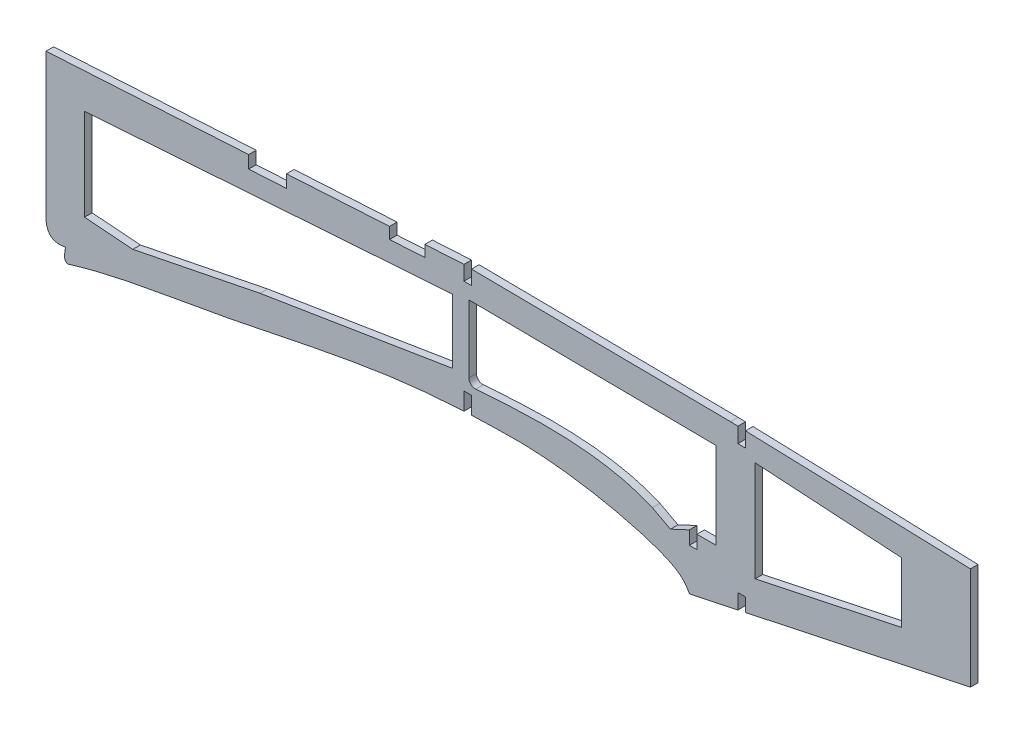
SolidWorks part; units mm, degrees
ref_plane "Front Plane" through (0, 0, 0) normal (0, 0, 1) x (1, 0, 0)
ref_plane "Top Plane" through (0, 0, 0) normal (0, 1, 0) x (1, 0, 0)
ref_plane "Right Plane" through (0, 0, 0) normal (1, 0, 0) x (0, 0, -1)
sketch "Sketch1" plane through (0, 0, 0) normal (0, 0, 1) x (1, 0, 0)
  line L0 (0, 0) -> (110, 0) construction
  line L1 (110, 0) -> (110, 21) construction
  line L2 (0, 0) -> (110, 21)
  line L3 (23.5, 17.3139) -> (20, 16.6457)
  line L4 (0, 0) -> (20, 0)
  line L5 (20, 0) -> (20, 67.15) construction
  line L6 (0, 0) -> (0, 67.15) construction
  line L7 (0, 67.15) -> (110, 67.15) construction
  line L8 (110, 61.55) -> (110, 67.15)
  line L9 (0, 67.15) -> (110, 61.55)
  line L10 (23.5, 53.9381) -> (81.5, 50.9854)
  line L11 (81.5, 50.9854) -> (81.5, 28.3866)
  line L12 (23.5, 53.9381) -> (23.5, 17.3139)
  line L13 (23.5, 17.3139) -> (81.5, 28.3866)
  line L14 (110, 21) -> (110, 61.55) construction
  line L15 (112, 61.4482) -> (112, 21.3818)
  line L16 (110, 61.55) -> (112, 61.4482)
  line L17 (110, 21) -> (112, 21.3818)
  line L18 (10.9, 67.15) -> (10.9, 0)
  line L19 (0, 67.15) -> (-82.3902, 71.3444)
  line L20 (0, 0) -> (-182.0672, -34.7583)
  line L21 (-86.7, -36.2944) -> (-86.7, -57.7944)
  line L22 (-93.05, 89.1409) -> (-93.05, -40.6456)
  line L23 (-70.5516, 60.184) -> (7.4462, 55.0566)
  line L24 (-89.4413, 54.3923) -> (-89.4413, 37.6042)
  line L25 (-65.3332, 22.0194) -> (-42.2468, 20.2821) construction
  line L26 (-42.2468, 20.2821) -> (-21.4079, 14.5616) construction
  line L27 (-21.4079, 14.5616) -> (-8.5368, 8.8411) construction
  line L28 (-8.5368, 8.8411) -> (-2.8162, 7.0023) construction
  line L29 (-2.8162, 7.0023) -> (0, 0) construction
  line L30 (-235.9653, 18.0968) -> (-234.0715, 53.1142)
  line L31 (-238.05, 59.4719) -> (-238.05, 21) construction
  line L32 (-921.7383, -124.7627) -> (144.2786, -161.9889) construction
  line L34 (-226.3459, 60.184) -> (-104.3294, 60.184)
  line L35 (-82.0567, 37.6042) -> (-82.7237, 57.9466)
  line L36 (-82.3902, 71.3444) -> (-103.6, 72.4242)
  line L37 (-103.6, 72.4242) -> (-103.6, 67.1242)
  line L38 (-103.6, 67.1242) -> (-117.6, 67.1242)
  line L39 (-117.6, 67.1242) -> (-117.6, 72.6011)
  line L40 (-117.6, 72.6011) -> (-158.5, 72.6011)
  line L41 (-158.5, 72.6011) -> (-158.5, 68.6011)
  line L42 (-158.5, 68.6011) -> (-173.5, 69.3647)
  line L43 (-173.5, 69.3647) -> (-173.5, 73.3311)
  line L44 (-173.5, 73.3311) -> (-250.6778, 73.3311)
  line L45 (-250.6778, 73.3311) -> (-251.1351, 64.35)
  line L46 (-251.1351, 64.35) -> (-249.1426, 59.4719)
  line L47 (-249.1426, 59.4719) -> (-253.0614, 11.9612)
  spline_without_curve S0
  spline S1 degree 3 poles (-62.7428, 33.1676) (-50.008, 31.9642) (-31.0962, 32.5015) (-14.1751, 24.9914) (-9.6822, 22.192) knots 0 0 0 0 0.709755 1 1 1 1
  spline S2 degree 3 poles (-9.6822, 22.192) (-6.8917, 20.9668) (-4.0654, 23.2801) (1.077, 24.0309) (6.7349, 23.1276) (13.0796, 25.9871) (10.9, 30.3114) knots 0 0 0 0 0.304362 0.391412 0.603771 1 1 1 1
  spline S3 degree 3 poles (-65.3332, 22.0194) (-77.4805, 22.6509) (-98.8967, 23.1079) (-139.7694, 19.7032) (-187.7649, 10.9991) (-227.3069, 7.5749) (-246.6861, 2.6333) knots 0 0 0 0 0.199692 0.351003 0.672194 1 1 1 1
  spline S4 degree 3 poles (-62.7428, 33.1676) (-67.9368, 33.6388) (-74.1452, 31.6619) (-82.8627, 34.4448) (-82.0567, 37.6042) knots 0 0 0 0 0.65977 1 1 1 1
  spline S5 degree 3 poles (-104.3294, 60.184) (-100.5301, 59.5513) (-93.8007, 61.9485) (-88.7866, 56.5953) (-89.4413, 54.3923) knots 0 0 0 0 0.661964 1 1 1 1
  spline S6 degree 3 poles (-104.3294, 33.547) (-100.6826, 33.3941) (-97.3824, 32.6768) (-91.1309, 33.381) (-89.6784, 34.473) (-89.4413, 37.6042) knots 0 0 0 0 0.555991 0.846219 1 1 1 1
  spline S7 degree 3 poles (-104.3294, 33.547) (-116.4931, 34.3961) (-139.9294, 30.8214) (-169.9623, 27.1478) (-193.8607, 26.9431) (-204.0402, 24.0023) (-211.1217, 23.2564) (-214.8026, 19.376) (-215.2918, 15.9456) (-214.9447, 14.6164) (-218.1891, 14.6988) (-221.7312, 14.9192) (-230.6867, 16.3937) (-236.4685, 15.9971) (-235.9653, 18.0968) knots 0 0 0 0 0.241116 0.431915 0.666521 0.747659 0.783153 0.799752 0.821748 0.858269 0.866885 0.907914 0.932706 1 1 1 1
  spline S8 degree 3 poles (-82.7237, 57.9466) (-82.8248, 63.2577) (-71.0235, 59.3637) (-70.5516, 60.184) knots 0 0 0 0 1 1 1 1
  spline S9 degree 2 poles (7.4462, 55.0566) (12.5645, 55.8042) (10.9, 50.909) knots 0 0 0 1 1 1
  spline S10 degree 3 poles (-234.0715, 53.1142) (-234.3359, 55.4474) (-232.0516, 60.1047) (-228.0459, 60.2249) (-226.3459, 60.184) knots 0 0 0 0 0.618254 1 1 1 1
  spline S11 degree 2 poles (-253.0614, 11.9612) (-252.6953, 7.068) (-247.464, 8.0018) knots 0 0 0 1 1 1
  spline S12 degree 3 poles (-246.6861, 2.6333) (-248.9283, 3.1544) (-247.5659, 6.6016) (-247.464, 8.0018) knots 0 0 0 0 1 1 1 1
  point P55 (-93.05, 46.4253)
  dimension "D1" = 110
  dimension "D2" = 21
  dimension "D3" = 12.6
  dimension "D4" = 20
  dimension "D5" = 67.15
  dimension "D6" = 5.6
  dimension "D7" = 110
  dimension "D8" = 12
  dimension "D9" = 3.5
  dimension "D10" = 58
  dimension "D11" = 2
  dimension "D12" = 12.6
  dimension "D13" = 97.6
  dimension "D14" = 6.35
  dimension "D15" = 14
  dimension "D16" = 145
  dimension "D17" = 15
  dimension "D18" = 40.9
  dimension "D19" = 10.55
  dimension "D20" = 5.3
  dimension "D21" = 4
sketch "Sketch2" plane through (0, 0, 0) normal (0, 0, 1) x (1, 0, 0)
  line L0 (0, 0) -> (110, 21) construction
  line L1 (0, 0) -> (110, 21)
  line L2 (112, 61.4482) -> (112, 21.3818) construction
  line L3 (112, 61.4482) -> (112, 21.3818)
  line L4 (-70.5516, 60.184) -> (7.4462, 55.0566) construction
  line L5 (110, 21) -> (112, 21.3818) construction
  line L6 (110, 21) -> (112, 21.3818)
  line L7 (110, 61.55) -> (112, 61.4482) construction
  line L8 (110, 61.55) -> (112, 61.4482)
  line L9 (0, 67.15) -> (110, 61.55) construction
  line L10 (0, 67.15) -> (110, 61.55)
  line L11 (0, 67.15) -> (-82.3902, 71.3444) construction
  line L12 (0, 67.15) -> (-82.3902, 71.3444)
  line L13 (-82.3902, 71.3444) -> (-103.6, 72.4242) construction
  line L14 (-82.3902, 71.3444) -> (-103.6, 72.4242)
  line L15 (-103.6, 72.4242) -> (-103.6, 67.3782)
  line L16 (-103.6, 67.3782) -> (-117.6, 67.3782)
  line L17 (-117.6, 67.3782) -> (-117.6, 72.6011)
  line L18 (-117.6, 72.6011) -> (-158.5, 72.6011)
  line L19 (-158.5, 72.6011) -> (-158.5, 69.3647)
  line L20 (-158.5, 69.3647) -> (-173.5, 69.3647)
  line L21 (-173.5, 69.3647) -> (-173.5, 73.3311)
  line L22 (-173.5, 73.3311) -> (-250.6778, 73.3311) construction
  line L23 (-173.5, 73.3311) -> (-250.6778, 73.3311)
  line L24 (-250.6778, 73.3311) -> (-253.0614, 11.9612)
  line L25 (-89.4413, 54.3923) -> (-89.4413, 37.6042) construction
  line L26 (-226.3459, 60.184) -> (-104.3294, 60.184) construction
  line L27 (-235.9653, 18.0968) -> (-234.0715, 53.1142) construction
  line L28 (-89.4413, 54.3923) -> (-89.4413, 37.6042)
  line L29 (-226.3459, 60.184) -> (-104.3294, 60.184)
  line L30 (-235.9653, 18.0968) -> (-234.0715, 53.1142)
  line L31 (-82.0567, 37.6042) -> (-82.7237, 57.9466) construction
  line L32 (-70.5516, 60.184) -> (7.4462, 55.0566)
  line L33 (-82.0567, 37.6042) -> (-82.7237, 57.9466)
  line L34 (10.9, 50.909) -> (10.9, 30.3114)
  line L35 (81.5, 50.9854) -> (81.5, 28.3866) construction
  line L36 (23.5, 17.3139) -> (81.5, 28.3866) construction
  line L37 (23.5, 53.9381) -> (81.5, 50.9854) construction
  line L38 (23.5, 53.9381) -> (23.5, 17.3139) construction
  line L39 (81.5, 48.1342) -> (81.5, 30.8681)
  line L40 (27.0626, 17.994) -> (79.0626, 27.9213)
  line L41 (26.6525, 53.7776) -> (78.6525, 51.1303)
  line L42 (23.5, 50.7815) -> (23.5, 20.9408)
  line L43 (-158.5, 72.6011) -> (-158.5, 68.6011) construction
  arc A0 (26.6525, 53.7776) -> (23.5, 50.7815) centre (26.5, 50.7815) ccw
  arc A1 (27.0626, 17.994) -> (23.5, 20.9408) centre (26.5, 20.9408) cw
  arc A2 (81.5, 30.8681) -> (79.0626, 27.9213) centre (78.5, 30.8681) cw
  arc A3 (81.5, 48.1342) -> (78.6525, 51.1303) centre (78.5, 48.1342) ccw
  parabola Q0 (-253.0614, 11.9612) -> (-247.464, 8.0018) focus (-250.6889, 9.8561) apex (-251.6748, 8.6753) construction
  parabola Q1 (-253.0614, 11.9612) -> (-247.464, 8.0018) focus (-250.6889, 9.8561) apex (-251.6748, 8.6753)
  parabola Q2 (7.4462, 55.0566) -> (10.9, 50.909) focus (10.2347, 53.865) apex (10.8693, 54.3929) construction
  parabola Q3 (7.4462, 55.0566) -> (10.9, 50.909) focus (10.2347, 53.865) apex (10.8693, 54.3929)
  spline S0 degree 3 poles (1215.9924, 1366.2087) (-1689.2719, -1445.9602) (1160.7038, 1491.2702) (-1612.7605, -1453.4516) knots -5.972872 -5.972872 -5.972872 -5.972872 7.300913 7.300913 7.300913 7.300913 only from (-246.6861, 2.6333) to (-247.464, 8.0018) construction
  spline S1 degree 3 poles (-246.6861, 2.6333) (-248.9283, 3.1544) (-247.5659, 6.6016) (-247.464, 8.0018) knots 0 0 0 0 1 1 1 1
  spline S2 degree 3 poles (175.3636, 1967.872) (391.9741, -245.9956) (130.7811, 42.2402) (-139.7694, 19.7032) (-325.1272, -13.9116) (-514.1452, 28.671) (-309.5796, -1983.4136) knots -3.777296 -3.777296 -3.777296 -3.777296 0.199692 0.351003 0.672194 3.290466 3.290466 3.290466 3.290466 only from (-65.3332, 22.0194) to (-246.6861, 2.6333) construction
  spline S3 degree 3 poles (-65.3332, 22.0194) (-77.4805, 22.6509) (-98.8967, 23.1079) (-139.7694, 19.7032) (-187.7649, 10.9991) (-227.3069, 7.5749) (-246.6861, 2.6333) knots 0 0 0 0 0.199692 0.351003 0.672194 1 1 1 1
  spline S4 degree 5 poles (1876.0426, 360.0904) (-1729.8867, -1179.746) (583.5253, 1803.2982) (78.4446, -2000.9415) (-313.5377, 2017.6127) (349.0217, -1969.1752) knots -2.469726 -2.469726 -2.469726 -2.469726 -2.469726 -2.469726 2.883008 2.883008 2.883008 2.883008 2.883008 2.883008 only from (-65.3332, 22.0194) to (0, 0) construction
  spline S5 degree 5 poles (-65.3332, 22.0194) (-42.2468, 20.2821) (-21.4079, 14.5616) (-8.5368, 8.8411) (-2.8162, 7.0023) (0, 0) knots 0 0 0 0 0 0 1 1 1 1 1 1
  spline S6 degree 3 poles (-2003.4226, -592.8129) (-74.6134, 83.2569) (-127.2178, 29.3158) (-83.3934, 34.2526) (-91.8628, 46.616) (-191.2637, 2034.7775) knots -4.772522 -4.772522 -4.772522 -4.772522 0.555991 0.846219 2.237697 2.237697 2.237697 2.237697 only from (-104.3294, 33.547) to (-89.4413, 37.6042) construction
  spline S7 degree 3 poles (-884.1428, -1800.4231) (147.9483, 84.9453) (-58.8059, 40.7444) (-169.9623, 27.1478) (-193.8607, 26.9431) (-204.0402, 24.0023) (-211.1217, 23.2564) (-214.8026, 19.376) (-215.2918, 15.9456) (-214.9447, 14.6164) (-218.1891, 14.6988) (-221.7312, 14.9192) (-259.045, 21.0628) (-280.7399, -17.3172) (1437.9042, 1112.0112) knots -1.800378 -1.800378 -1.800378 -1.800378 0.241116 0.431915 0.666521 0.747659 0.783153 0.799752 0.821748 0.858269 0.866885 0.907914 0.932706 1.421519 1.421519 1.421519 1.421519 only from (-104.3294, 33.547) to (-235.9653, 18.0968) construction
  spline S8 degree 3 poles (879.86, 1711.5652) (-207.6215, -132.0929) (-295.8251, 232.0271) (-122.4858, -93.2389) (-314.6686, 2056.7417) knots -5.484197 -5.484197 -5.484197 -5.484197 0.618254 6.842445 6.842445 6.842445 6.842445 only from (-234.0715, 53.1142) to (-226.3459, 60.184) construction
  spline S9 degree 3 poles (-104.3294, 33.547) (-100.6826, 33.3941) (-97.3824, 32.6768) (-91.1309, 33.381) (-89.6784, 34.473) (-89.4413, 37.6042) knots 0 0 0 0 0.555991 0.846219 1 1 1 1
  spline S10 degree 3 poles (-104.3294, 33.547) (-116.4931, 34.3961) (-139.9294, 30.8214) (-169.9623, 27.1478) (-193.8607, 26.9431) (-204.0402, 24.0023) (-211.1217, 23.2564) (-214.8026, 19.376) (-215.2918, 15.9456) (-214.9447, 14.6164) (-218.1891, 14.6988) (-221.7312, 14.9192) (-230.6867, 16.3937) (-236.4685, 15.9971) (-235.9653, 18.0968) knots 0 0 0 0 0.241116 0.431915 0.666521 0.747659 0.783153 0.799752 0.821748 0.858269 0.866885 0.907914 0.932706 1 1 1 1
  spline S11 degree 3 poles (-234.0715, 53.1142) (-234.3359, 55.4474) (-232.0516, 60.1047) (-228.0459, 60.2249) (-226.3459, 60.184) knots 0 0 0 0 0.618254 1 1 1 1
  spline S12 degree 3 poles (319.5224, 2014.3086) (-192.9155, -111.4852) (-73.7068, 193.2347) (-74.1309, -42.5933) (-2079.8517, 234.6153) knots -4.398535 -4.398535 -4.398535 -4.398535 0.661964 3.952777 3.952777 3.952777 3.952777 only from (-104.3294, 60.184) to (-89.4413, 54.3923) construction
  spline S13 degree 3 poles (-104.3294, 60.184) (-100.5301, 59.5513) (-93.8007, 61.9485) (-88.7866, 56.5953) (-89.4413, 54.3923) knots 0 0 0 0 0.661964 1 1 1 1
  spline S14 degree 3 poles (-476.921, 1966.6082) (-22.6367, -59.8265) (-22.4132, 20.601) (1.077, 24.0309) (25.1351, 20.1898) (79.5245, 97.6802) (-1928.1805, 515.6228) knots -2.154256 -2.154256 -2.154256 -2.154256 0.304362 0.391412 0.603771 3.262307 3.262307 3.262307 3.262307 only from (-9.6822, 22.192) to (10.9, 30.3114) construction
  spline S15 degree 3 poles (290.3742, 1996.6931) (-276.3479, -157.1226) (45.2421, 284.1781) (112.1059, -304.2564) (-1943.388, -409.2218) knots -4.781032 -4.781032 -4.781032 -4.781032 0.709755 6.530859 6.530859 6.530859 6.530859 only from (-62.7428, 33.1676) to (-9.6822, 22.192) construction
  spline S16 degree 3 poles (1014.7339, -1650.8552) (-65.1434, 157.9827) (-20.1321, -37.6544) (-136.3103, 72.496) (1711.8022, 920.8151) knots -4.712693 -4.712693 -4.712693 -4.712693 0.65977 3.302586 3.302586 3.302586 3.302586 only from (-62.7428, 33.1676) to (-82.0567, 37.6042) construction
  spline S17 degree 3 poles (1566.4817, -1072.7309) (-1852.9005, 1150.0589) (1734.6604, -974.3467) (-1819.0286, 1030.9337) knots -3.685572 -3.685572 -3.685572 -3.685572 4.790703 4.790703 4.790703 4.790703 only from (-82.7237, 57.9466) to (-70.5516, 60.184) construction
  spline S18 degree 3 poles (-9.6822, 22.192) (-6.8917, 20.9668) (-4.0654, 23.2801) (1.077, 24.0309) (6.7349, 23.1276) (13.0796, 25.9871) (10.9, 30.3114) knots 0 0 0 0 0.304362 0.391412 0.603771 1 1 1 1
  spline S19 degree 3 poles (-62.7428, 33.1676) (-50.008, 31.9642) (-31.0962, 32.5015) (-14.1751, 24.9914) (-9.6822, 22.192) knots 0 0 0 0 0.709755 1 1 1 1
  spline S20 degree 3 poles (-62.7428, 33.1676) (-67.9368, 33.6388) (-74.1452, 31.6619) (-82.8627, 34.4448) (-82.0567, 37.6042) knots 0 0 0 0 0.65977 1 1 1 1
  spline S21 degree 3 poles (-82.7237, 57.9466) (-82.8248, 63.2577) (-71.0235, 59.3637) (-70.5516, 60.184) knots 0 0 0 0 1 1 1 1
  point P6 (-2.1894, 23.46)
  dimension "D1" = 3
  dimension "D2" = 3
  dimension "D3" = 14
sketch "Sketch3" plane through (0, 0, 0) normal (0, 0, -1) x (-1, 0, 0)
  line L0 (-20, 0) -> (-20, 67.15) construction
  line L1 (-20, 0) -> (-20, 67.15)
  line L2 (0, 67.15) -> (-110, 61.55) construction
  line L3 (0, 23.8107) -> (0, -7.1001) construction
  line L4 (0, 67.15) -> (-110, 61.55)
  line L5 (-17, 66.2845) -> (-17, 60.5845)
  line L6 (-17, 60.5845) -> (-20, 60.5845)
  line L7 (-20, 60.5845) -> (-20, 66.1318)
  line L8 (-20, 66.1318) -> (-17, 66.2845)
  line L9 (0, 0) -> (-110, 21) construction
  line L10 (0, 0) -> (-110, 21)
  line L11 (-17, 8.7455) -> (-17, 3.2455)
  line L12 (-17, 8.7455) -> (-20, 8.7455)
  line L13 (-20, 8.7455) -> (-20, 3.7748)
  line L14 (-20, 3.7748) -> (-17, 3.2455)
  line L15 (88, 71.63) -> (88, 66.2827)
  line L16 (91, 71.7827) -> (91, 66.2827)
  line L17 (82.3902, 71.3444) -> (103.6, 72.4242) construction
  line L18 (91, 66.2827) -> (88, 66.2827)
  line L19 (88, 71.63) -> (91, 71.7827)
  line L24 (0, 23.8107) -> (0, 17.8107)
  line L25 (-3, 23.7752) -> (-3, 17.8107)
  line L26 (0, 17.8107) -> (-3, 17.8107)
  line L27 (-3, 23.7752) -> (0, 23.8107)
  line L28 (88, 160.3101) -> (88, -51.3247)
  line L30 (91, 29.1781) -> (91, 22.6781)
  line L31 (91, 29.1781) -> (88, 29.1781)
  line L32 (88, 29.1781) -> (88, 22.6781)
  line L33 (88, 22.6781) -> (91, 22.6781)
  spline S1 degree 3 poles (9.6822, 22.192) (6.8917, 20.9668) (4.0654, 23.2801) (-1.077, 24.0309) (-6.7349, 23.1276) (-13.0796, 25.9871) (-10.9, 30.3114) knots 0 0 0 0 0.304362 0.391412 0.603771 1 1 1 1 construction
  spline S2 degree 3 poles (65.3332, 22.0194) (77.4805, 22.6509) (98.8967, 23.1079) (139.7694, 19.7032) (187.7649, 10.9991) (227.3069, 7.5749) (246.6861, 2.6333) knots 0 0 0 0 0.199692 0.351003 0.672194 1 1 1 1 construction
  dimension "D1" = 3
  dimension "D2" = 5.7
  dimension "D3" = 5.5
  dimension "D4" = 6.5
  dimension "D5" = 3
  dimension "D6" = 5.5
  dimension "D7" = 108
  dimension "D8" = 20
  dimension "D9" = 6
  dimension "D10" = 3
sketch "Sketch4" plane through (0, 0, 0) normal (0, 0, -1) x (-1, 0, 0)
  line L0 (119.2548, -0.35) -> (-119.2548, -0.35)
  line L1 (0, -0.35) -> (0, 67.15)
  line L57 (253.3406, -1.2994) -> (254.1722, 60.1111)
  line L58 (254.1722, 60.1111) -> (174.8745, 64.2669)
  line L59 (174.8745, 64.2669) -> (174.8979, 65.3912)
  line L60 (174.8979, 65.3912) -> (159.85, 57.5564)
  line L61 (159.85, 57.5564) -> (159.9757, 68.9387)
  line L62 (159.9757, 68.9387) -> (119.0846, 69.7894)
  line L63 (119.0846, 69.7894) -> (118.9759, 64.5677)
  line L64 (118.9759, 64.5677) -> (104.979, 64.8589)
  line L65 (104.979, 64.8589) -> (105.0839, 69.9038)
  line L66 (105.0839, 69.9038) -> (89.4708, 69.4342)
  line L70 (89.4708, 69.4342) -> (-15.6177, 66.2738)
  line L74 (-15.6177, 66.2738) -> (-110.6977, 63.4144)
  line L75 (-110.6977, 63.4144) -> (-111.5311, 23.3567)
  line L76 (-111.5311, 23.3567) -> (0, -0.35)
  parabola Q2 (247.5437, -4.9604) -> (253.3406, -1.2994) focus (250.8611, -3.2775) apex (251.7839, -4.5082)
  spline S8 degree 3 poles (66.396, 18.2199) (74.9521, 18.2164) (83.5166, 18.0283) (92.0622, 17.5345) knots 0.875946 0.875946 0.875946 0.875946 1.016409 1.016409 1.016409 1.016409
  spline S9 degree 3 poles (92.0622, 17.5345) (95.666, 17.3341) (108.4649, 16.4288) (140.621, 12.1175) (188.1196, 1.0175) (227.4402, -4.3854) (246.5472, -10.2927) knots 0 0 0 0 0.059228 0.210539 0.53173 0.859537 0.859537 0.859537 0.859537
  spline S10 degree 3 poles (246.5472, -10.2927) (248.8088, -9.8636) (247.5883, -6.3636) (247.5437, -4.9604) knots 0 0 0 0 1 1 1 1
  spline S11 degree 5 poles (0, -0.35) (3.1789, 6.4953) (8.9878, 8.0322) (22.1406, 13.0712) (43.2504, 17.6932) (66.396, 18.2199) knots 0 0 0 0 0 0 1 1 1 1 1 1
  point P0 (159.85, 57.5564)
  point P3 (0, -0.35)
  point P4 (0, -0.35)
  point P15 (0, 0)
  dimension "D1" = 12
  dimension "D2" = 67.5
sketch "Sketch6" plane through (0, 0, -3) normal (0, 0, -1) x (-1, 0, 0)
  line L0 (0, -81.2122) -> (0, 80.5122) construction
  line L1 (-10.5, 55.95) -> (87.47, 56.9492)
  line L2 (-10.5, 55.95) -> (-10.5, 21.65)
  line L3 (-3, 21.65) -> (-10.5, 21.65)
  line L4 (0, 21.65) -> (0, 16.35)
  line L5 (0, 16.35) -> (-3, 16.35)
  line L6 (-3, 21.65) -> (-3, 16.35)
  line L7 (0, 21.65) -> (7.5224, 18.1423)
  line L8 (7.5224, 18.1423) -> (14.7017, 21.9596)
  line L9 (87.47, 56.9492) -> (87.47, 30.1297)
  line L10 (87.47, 27.441) -> (87.47, 17.771) construction
  line L11 (78.3036, 17.771) -> (96.6364, 17.771) construction
  line L12 (0, -0.35) -> (-19.25, 3.7417)
  line L13 (104.95, 67.267) -> (104.95, 62.7594)
  line L14 (-16.3334, 66.995) -> (86.45, 68.0433)
  line L15 (-26.1, 57.7585) -> (-26.1, 17.8747)
  line L16 (-111.5311, 23.3567) -> (0, -0.35) construction
  line L17 (-19.25, 66.904) -> (-19.25, 60.904)
  line L18 (-111.5311, 23.3567) -> (-22.25, 4.3794)
  line L19 (118.95, 66.4512) -> (118.95, 61.9436)
  line L21 (-19.25, 9.7417) -> (-19.25, 3.7417)
  line L25 (-19.25, 66.904) -> (-19.25, 60.904)
  line L26 (-19.25, 60.904) -> (-22.25, 60.904)
  line L27 (-22.25, 66.8105) -> (-22.25, 60.904)
  line L28 (-111.5311, 23.3567) -> (-111.5311, 64.0267)
  line L29 (86.45, 82.6833) -> (86.45, 9.104) construction
  line L30 (104.95, 62.7594) -> (118.95, 61.9436)
  line L32 (86.45, 68.0433) -> (86.45, 62.3703)
  line L33 (86.45, 62.3703) -> (89.45, 62.3703)
  line L34 (89.45, 68.1703) -> (89.45, 62.3703)
  line L35 (86.45, 17.6703) -> (89.45, 17.6703)
  line L36 (86.45, 17.6703) -> (86.45, 24.6703)
  line L37 (86.45, 24.6703) -> (89.45, 24.6703)
  line L38 (89.45, 17.6703) -> (89.45, 24.6703)
  line L39 (159.85, 64.0678) -> (159.85, 59.0593)
  line L40 (174.85, 63.1937) -> (174.85, 58.1852)
  line L41 (159.85, 59.0593) -> (174.85, 58.1852)
  line L42 (-16.3334, 66.995) -> (-19.25, 66.904)
  line L43 (93.97, 55.6703) -> (93.97, 30.1703)
  line L44 (239.97, 45.4839) -> (239.97, 9.104)
  line L45 (255.27, 1.5316) -> (255.27, 58.5073)
  line L46 (239.97, 45.4839) -> (93.97, 55.6703)
  line L47 (239.97, 9.104) -> (220.8231, 7.6436)
  line L48 (220.8231, 7.6436) -> (170.3292, 17.771)
  line L49 (170.3292, 17.771) -> (93.97, 30.1703)
  line L50 (-26.1, 17.8747) -> (-84.1, 30.203)
  line L51 (-84.1, 30.203) -> (-84.1, 54.203)
  line L52 (-26.1, 57.7585) -> (-84.1, 54.203)
  line L53 (118.95, 66.4512) -> (159.85, 64.0678)
  line L54 (174.85, 63.1937) -> (255.27, 58.5073)
  line L55 (-19.25, 9.7417) -> (-19.25, 3.7417)
  line L56 (-19.25, 9.7417) -> (-22.25, 9.7417)
  line L57 (-22.25, 9.7417) -> (-22.25, 4.3794)
  line L58 (-22.25, 66.8105) -> (-111.5311, 64.0267)
  line L59 (264.7519, 58.5073) -> (255.27, 58.5073)
  line L60 (89.45, 68.1703) -> (255.27, 58.5073) construction
  line L61 (89.45, 68.1703) -> (104.95, 67.267)
  arc A1 (84.7894, 27.6362) -> (87.47, 30.1297) centre (84.97, 30.1297) ccw
  parabola Q0 (247.5437, -4.9604) -> (253.3406, -1.2994) focus (250.8611, -3.2775) apex (251.7839, -4.5082) construction
  parabola Q1 (247.5437, -4.9604) -> (253.1636, -2.2399) focus (250.8611, -3.2775) apex (251.7839, -4.5082)
  parabola Q2 (247.5437, -4.9604) -> (253.3406, -1.2994) focus (250.8611, -3.2775) apex (251.7839, -4.5082) construction
  spline S0 degree 3 poles (-77.6637, 1965.2461) (-403.1026, -225.9067) (-128.1526, 48.1531) (140.621, 12.1175) (324.0581, -30.7502) (514.9719, 2.2988) (209.7722, -1996.9316) knots -3.912695 -3.912695 -3.912695 -3.912695 0.059228 0.210539 0.53173 3.149975 3.149975 3.149975 3.149975 only from (92.0622, 17.5345) to (246.5472, -10.2927) construction
  spline S1 degree 3 poles (7.5224, 18.1423) (15.8431, 23.4586) (31.7661, 27.749) (54.2955, 29.2195) (70.8321, 28.623) (81.0266, 27.9088) (84.7894, 27.6362) knots 0 0 0 0 0.360279 0.59219 0.828481 0.967074 0.967074 0.967074 0.967074
  spline S2 degree 3 poles (-72.1435, 1973.9319) (-667.3868, -1967.4883) (657.6539, 2002.3942) (321.1173, -1939.6078) knots -2.901307 -2.901307 -2.901307 -2.901307 4.225484 4.225484 4.225484 4.225484 only from (66.396, 18.2199) to (92.0622, 17.5345) construction
  spline S3 degree 5 poles (-451.6238, -1948.659) (418.7135, 1998.167) (-183.0533, -1994.4986) (-488.3696, 1831.0433) (1665.7875, -1269.0189) (-1854.6198, 457.4284) knots -1.883035 -1.883035 -1.883035 -1.883035 -1.883035 -1.883035 3.469724 3.469724 3.469724 3.469724 3.469724 3.469724 only from (0, -0.35) to (66.396, 18.2199) construction
  spline S4 degree 5 poles (0, -0.35) (3.1789, 6.4953) (8.9878, 8.0322) (22.1406, 13.0712) (43.2504, 17.6932) (66.396, 18.2199) knots 0 0 0 0 0 0 1 1 1 1 1 1
  spline S5 degree 3 poles (66.396, 18.2199) (74.9521, 18.2164) (83.5166, 18.0283) (92.0622, 17.5345) knots 0.875946 0.875946 0.875946 0.875946 1.016409 1.016409 1.016409 1.016409
  spline S6 degree 3 poles (92.0622, 17.5345) (95.666, 17.3341) (108.4649, 16.4288) (140.621, 12.1175) (188.1196, 1.0175) (227.4402, -4.3854) (246.5472, -10.2927) knots 0 0 0 0 0.059228 0.210539 0.53173 0.859537 0.859537 0.859537 0.859537
  spline S7 degree 3 poles (-1159.2225, 1411.881) (1628.7687, -1516.593) (-1098.8724, 1534.5802) (1552.0151, -1520.9534) knots -5.972872 -5.972872 -5.972872 -5.972872 7.300913 7.300913 7.300913 7.300913 only from (246.5472, -10.2927) to (247.5437, -4.9604) construction
  spline S8 degree 3 poles (246.5472, -10.2927) (248.8088, -9.8636) (247.5883, -6.3636) (247.5437, -4.9604) knots 0 0 0 0 1 1 1 1
  spline S9 degree 3 poles (65.3332, 22.0194) (77.4805, 22.6509) (98.8967, 23.1079) (139.7694, 19.7032) (187.7649, 10.9991) (227.3069, 7.5749) (246.6861, 2.6333) knots 0 0 0 0 0.199692 0.351003 0.672194 1 1 1 1 construction
  spline S10 degree 2 poles (247.5437, -4.9604) (255.2529, -6.5389) (255.27, 1.5316) knots 0 0 0 1 1 1
  point P4 (0, -0.35)
  point P27 (87.47, 17.771)
  point P63 (239.97, 8.1979)
  point P64 (0, 0)
  point P68 (239.97, 27.294)
  point P72 (255.27, 30.0195)
  point P76 (216.1327, 8.1979)
  point P79 (216.5283, 8.1979)
  point P89 (239.97, 13.7721)
  point P91 (220.8231, 7.6436)
  point P95 (239.97, 9.104)
  point P96 (170.3292, 17.771)
  dimension "D5" = 34.3
  dimension "D12" = 5
  dimension "D1" = 22
  dimension "D2" = 3
  dimension "D3" = 5.3
  dimension "D4" = 10.5
  dimension "D6" = 25
  dimension "D7" = 8.3
  dimension "D8" = 28
  dimension "D9" = 97.97
  dimension "D10" = 18.5
  dimension "D11" = 9.67
  dimension "D13" = 87.47
  dimension "D14" = 8.75
  dimension "D15" = 3
  dimension "D16" = 6
  dimension "D17" = 68.8
  dimension "D18" = 3
  dimension "D19" = 4.5
  dimension "D20" = 7
  dimension "D21" = 37.7
  dimension "D22" = 105.7
  dimension "D23" = 3
  dimension "D24" = 3
  dimension "D25" = 14
  dimension "D26" = 5
  dimension "D28" = 40.9
  dimension "D29" = 15
  dimension "D31" = 40.67
  dimension "D32" = 6.5
  dimension "D33" = 146
  dimension "D34" = 15.3
  dimension "D37" = 25.5
  dimension "D38" = 15.6
  dimension "D39" = 12.4
  dimension "D40" = 58
  dimension "D41" = 24
extrude "Boss-Extrude2" add sketch "Sketch6" along normal blind 3
